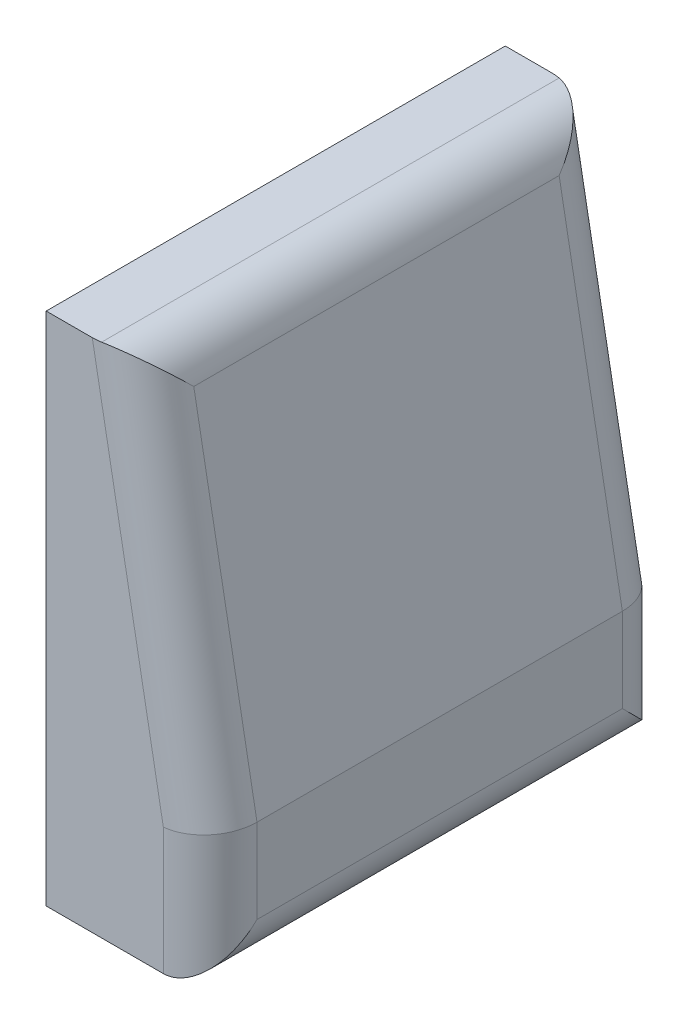
SolidWorks part; units mm, degrees
ref_plane "Front Plane" through (0, 0, 0) normal (0, 0, 1) x (1, 0, 0)
ref_plane "Top Plane" through (0, 0, 0) normal (0, 1, 0) x (1, 0, 0)
ref_plane "Right Plane" through (0, 0, 0) normal (1, 0, 0) x (0, 0, -1)
sketch "Sketch1" plane through (0, 0, 0) normal (0, 0, 1) x (1, 0, 0)
  line L0 (175, -442.1053) -> (175, -162.1053)
  line L1 (-175, 657.8947) -> (25, 657.8947)
  line L2 (-175, 657.8947) -> (-175, -442.1053)
  line L3 (-175, -442.1053) -> (175, -442.1053)
  line L5 (175, -162.1053) -> (25, 657.8947)
  point P0 (0, 0)
  dimension "D1" = 350
  dimension "D2" = 1100
  dimension "D4" = 280
  dimension "D5" = 200
extrude "Boss-Extrude1" add sketch "Sketch1" along normal mid plane 980
fillet "Fillet1" radius 100 6 edges at (25, 657.8947, 0) (175, -302.1053, 490) (100, 247.8947, -490) (175, -302.1053, -490) (175, -442.1053, 0) (100, 247.8947, 490)
